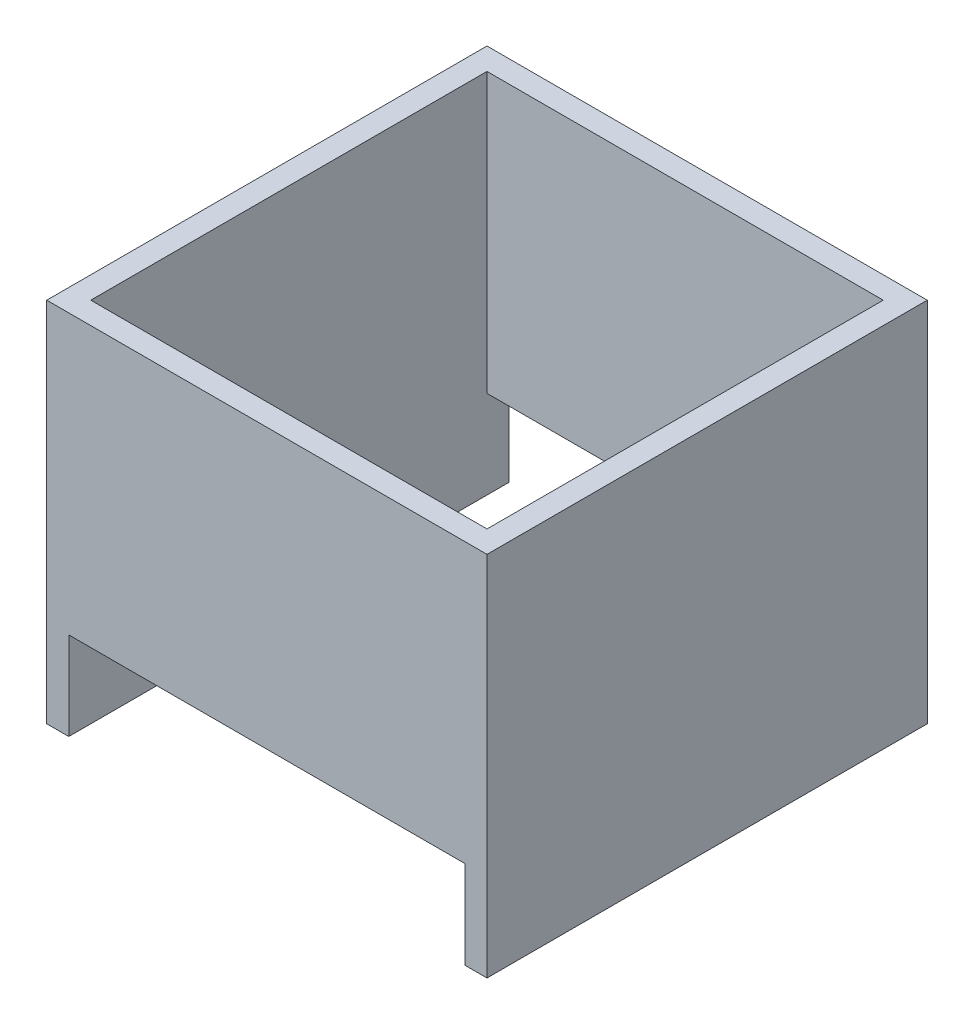
SolidWorks part; units mm, degrees
ref_plane "前视基准面" through (0, 0, 0) normal (0, 0, 1) x (1, 0, 0)
ref_plane "上视基准面" through (0, 0, 0) normal (0, 1, 0) x (1, 0, 0)
ref_plane "右视基准面" through (0, 0, 0) normal (1, 0, 0) x (0, 0, -1)
sketch "草图1" plane through (0, 0, 0) normal (0, 1, 0) x (1, 0, 0)
  line L1 (0, 0) -> (60, 0)
  line L2 (0, 0) -> (0, 60)
  line L3 (0, 60) -> (60, 60)
  line L4 (60, 0) -> (60, 60)
  point P5 (0, 0)
  point P7 (61.9048, 55.3968)
  dimension "D1" = 60
  dimension "D2" = 60
extrude "凸台-拉伸1" add sketch "草图1" along normal blind 50
sketch "草图2" plane through (0, 0, 0) normal (0, 1, 0) x (1, 0, 0)
  line L0 (0, 60) -> (0, 0) construction
  line L1 (3, 3) -> (57, 3)
  line L2 (3, 3) -> (3, 57)
  line L3 (3, 57) -> (57, 57)
  line L4 (57, 3) -> (57, 57)
  line L5 (60, 60) -> (0, 60) construction
  point P4 (0, 0)
  point P5 (0, 0)
  dimension "D1" = 54
  dimension "D2" = 54
  dimension "D3" = 3
  dimension "D4" = 3
extrude "切除-拉伸2" cut sketch "草图2" along normal through all
sketch "草图3" plane through (0, 0, 0) normal (0, 0, 1) x (1, 0, 0)
  line L1 (57, 0) -> (3, 0)
  line L2 (57, 0) -> (57, 12)
  line L3 (57, 12) -> (3, 12)
  line L4 (3, 0) -> (3, 12)
  dimension "D1" = 12
  dimension "D2" = 54
extrude "切除-拉伸3" cut sketch "草图3" against normal through all
